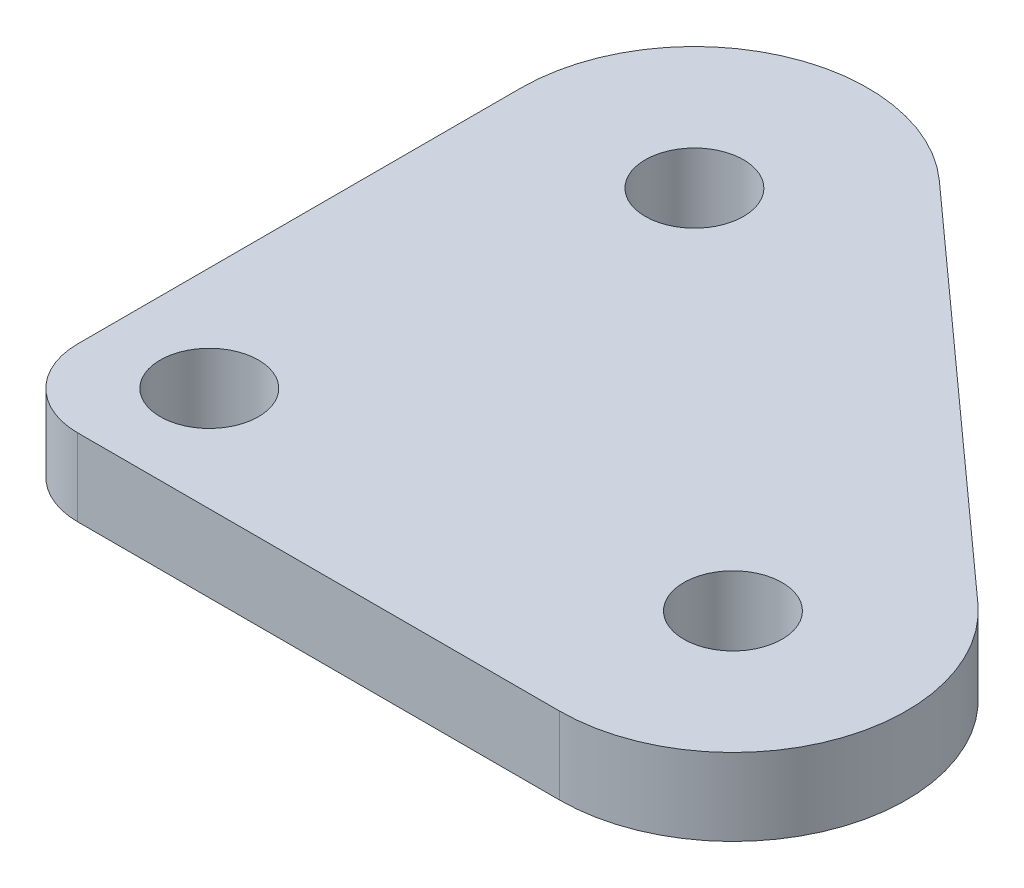
SolidWorks part; units mm, degrees
ref_plane "Front Plane" through (0, 0, 0) normal (0, 0, 1) x (1, 0, 0)
ref_plane "Top Plane" through (0, 0, 0) normal (0, 1, 0) x (1, 0, 0)
ref_plane "Right Plane" through (0, 0, 0) normal (1, 0, 0) x (0, 0, -1)
sketch "Sketch1" plane through (0, 0, 0) normal (0, 1, 0) x (1, 0, 0)
  line L0 (0, 0) -> (20, 0)
  line L1 (20, 0) -> (20, 18)
  line L2 (0, 0) -> (0, 18)
  line L3 (20, -9) -> (-9, -9)
  line L4 (-9, -9) -> (-9, 18)
  line L5 (6.0207, 24.6896) -> (26.0207, 6.6896)
  circle A0 centre (0, 18) radius 9
  circle A1 centre (20, 0) radius 9
  circle A2 centre (0, 18) radius 2.55
  circle A3 centre (20, 0) radius 2.55
  dimension "D4" = 18
  dimension "D5" = 18
  dimension "D6" = 5.1
  dimension "D7" = 5.1
  dimension "D1" = 20
  dimension "D2" = 18
  dimension "D3" = 18
extrude "Boss-Extrude1" add sketch "Sketch1" along normal blind 4
fillet "Fillet1" radius 4 1 edges at (-9, 2, 9)
sketch "Sketch2" plane through (0, 0, 0) normal (0, -1, 0) x (1, 0, 0)
  line L2 (-3.5858, 9) -> (-3.5858, 3.5858)
  line L3 (20, 9) -> (-5, 9) construction
  line L4 (-3.5858, 3.5858) -> (-9, 3.5858)
  line L5 (-9, 5) -> (-9, -18) construction
  circle A0 centre (-3.5858, 3.5858) radius 2.55
  arc A1 (-5, 9) -> (-9, 5) centre (-5, 5) ccw construction
  dimension "D1" = 5.1
  dimension "D2" = 2
extrude "Cut-Extrude1" cut sketch "Sketch2" against normal blind 4 contours L4 A0 L2 | L2 A0 L4
sketch "Sketch3" plane through (0, 4, 0) normal (0, 1, 0) x (1, 0, 0)
  line L0 (-3.5858, -3.5858) -> (20, 0)
  line L1 (20, 0) -> (-3.5858, 0)
  line L2 (-3.5858, 0) -> (-3.5858, -3.5858)
  line L3 (20, 0) -> (0, 18)
  line L4 (0, 18) -> (0, 0)
  line L5 (0, 0) -> (20, 0)
